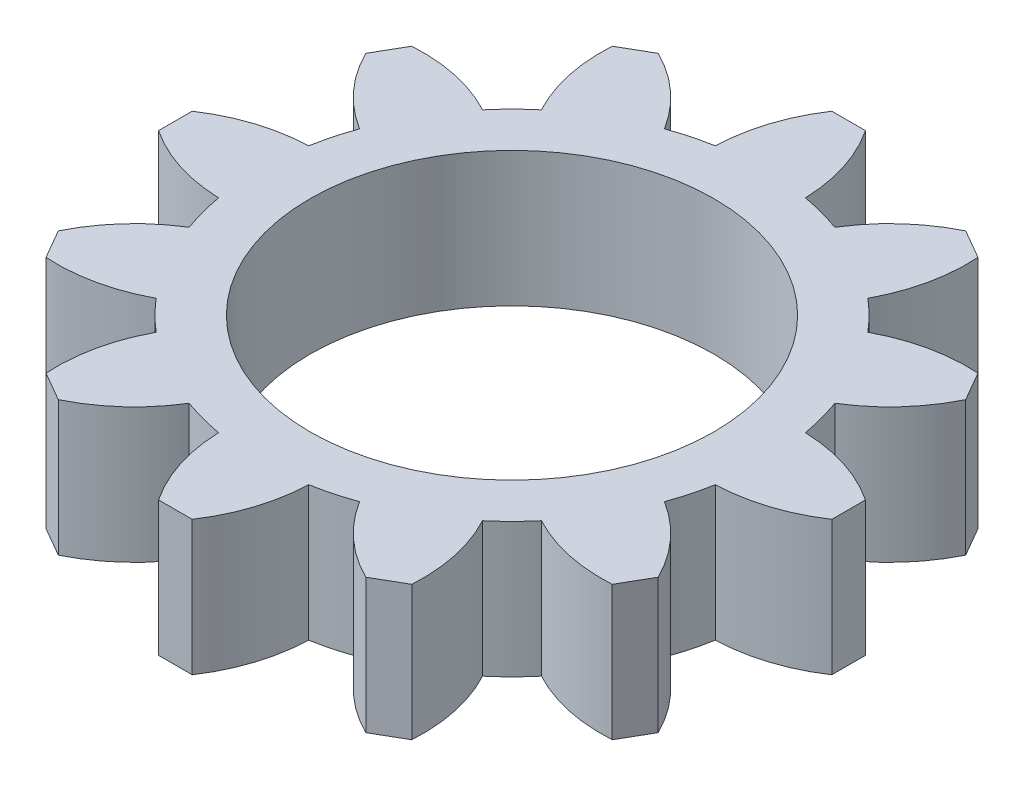
SolidWorks part; units mm, degrees
ref_plane "Front Plane" through (0, 0, 0) normal (0, 0, 1) x (1, 0, 0)
ref_plane "Top Plane" through (0, 0, 0) normal (0, 1, 0) x (1, 0, 0)
ref_plane "Right Plane" through (0, 0, 0) normal (1, 0, 0) x (0, 0, -1)
sketch "Sketch1" plane through (0, 0, 0) normal (0, 1, 0) x (1, 0, 0)
  line L0 (0, 12) -> (0, 21.8422) construction
  line L1 (-1, 20) -> (1, 20)
  line L2 (9.134, 17.8205) -> (10.866, 16.8205)
  line L3 (16.8205, 10.866) -> (17.8205, 9.134)
  line L4 (20, 1) -> (20, -1)
  line L5 (17.8205, -9.134) -> (16.8205, -10.866)
  line L6 (10.866, -16.8205) -> (9.134, -17.8205)
  line L7 (1, -20) -> (-1, -20)
  line L8 (-9.134, -17.8205) -> (-10.866, -16.8205)
  line L9 (-16.8205, -10.866) -> (-17.8205, -9.134)
  line L10 (-20, -1) -> (-20, 1)
  line L11 (-17.8205, 9.134) -> (-16.8205, 10.866)
  line L12 (-10.866, 16.8205) -> (-9.134, 17.8205)
  arc A0 (-2.675, 14.7596) -> (-5.0632, 14.1196) centre (0, 0) ccw
  circle A1 centre (0, 0) radius 12
  arc A2 (-1, 20) -> (-2.675, 14.7596) centre (7.3203, 14.4527) ccw
  arc A3 (1, 20) -> (2.675, 14.7596) centre (-7.3203, 14.4527) cw
  arc A4 (9.134, 17.8205) -> (5.0632, 14.1196) centre (13.5659, 8.8562) ccw
  arc A5 (10.866, 16.8205) -> (9.6964, 11.4446) centre (0.8868, 16.1765) cw
  arc A6 (16.8205, 10.866) -> (11.4446, 9.6964) centre (16.1765, 0.8868) ccw
  arc A7 (17.8205, 9.134) -> (14.1196, 5.0632) centre (8.8562, 13.5659) cw
  arc A8 (20, 1) -> (14.7596, 2.675) centre (14.4527, -7.3203) ccw
  arc A9 (20, -1) -> (14.7596, -2.675) centre (14.4527, 7.3203) cw
  arc A10 (17.8205, -9.134) -> (14.1196, -5.0632) centre (8.8562, -13.5659) ccw
  arc A11 (16.8205, -10.866) -> (11.4446, -9.6964) centre (16.1765, -0.8868) cw
  arc A12 (10.866, -16.8205) -> (9.6964, -11.4446) centre (0.8868, -16.1765) ccw
  arc A13 (9.134, -17.8205) -> (5.0632, -14.1196) centre (13.5659, -8.8562) cw
  arc A14 (1, -20) -> (2.675, -14.7596) centre (-7.3203, -14.4527) ccw
  arc A15 (-1, -20) -> (-2.675, -14.7596) centre (7.3203, -14.4527) cw
  arc A16 (-9.134, -17.8205) -> (-5.0632, -14.1196) centre (-13.5659, -8.8562) ccw
  arc A17 (-10.866, -16.8205) -> (-9.6964, -11.4446) centre (-0.8868, -16.1765) cw
  arc A18 (-16.8205, -10.866) -> (-11.4446, -9.6964) centre (-16.1765, -0.8868) ccw
  arc A19 (-17.8205, -9.134) -> (-14.1196, -5.0632) centre (-8.8562, -13.5659) cw
  arc A20 (-20, -1) -> (-14.7596, -2.675) centre (-14.4527, 7.3203) ccw
  arc A21 (-20, 1) -> (-14.7596, 2.675) centre (-14.4527, -7.3203) cw
  arc A22 (-17.8205, 9.134) -> (-14.1196, 5.0632) centre (-8.8562, 13.5659) ccw
  arc A23 (-16.8205, 10.866) -> (-11.4446, 9.6964) centre (-16.1765, 0.8868) cw
  arc A24 (-10.866, 16.8205) -> (-9.6964, 11.4446) centre (-0.8868, 16.1765) ccw
  arc A25 (-9.134, 17.8205) -> (-5.0632, 14.1196) centre (-13.5659, 8.8562) cw
  arc A26 (14.1196, -5.0632) -> (14.7596, -2.675) centre (0, 0) ccw
  arc A27 (14.7596, 2.675) -> (14.1196, 5.0632) centre (0, 0) ccw
  arc A28 (11.4446, 9.6964) -> (9.6964, 11.4446) centre (0, 0) ccw
  arc A29 (5.0632, 14.1196) -> (2.675, 14.7596) centre (0, 0) ccw
  arc A30 (-9.6964, 11.4446) -> (-11.4446, 9.6964) centre (0, 0) ccw
  arc A31 (-14.1196, 5.0632) -> (-14.7596, 2.675) centre (0, 0) ccw
  arc A32 (-14.7596, -2.675) -> (-14.1196, -5.0632) centre (0, 0) ccw
  arc A33 (-11.4446, -9.6964) -> (-9.6964, -11.4446) centre (0, 0) ccw
  arc A34 (-5.0632, -14.1196) -> (-2.675, -14.7596) centre (0, 0) ccw
  arc A35 (2.675, -14.7596) -> (5.0632, -14.1196) centre (0, 0) ccw
  arc A36 (9.6964, -11.4446) -> (11.4446, -9.6964) centre (0, 0) ccw
  point P80 (0, 0)
  dimension "D1" = 30
  dimension "D2" = 24
  dimension "D6" = 10
  dimension "D8" = 12
  dimension "D3" = 2
  dimension "D4" = 20
  dimension "D5" = 2
  dimension "D7" = 5.35
extrude "Boss-Extrude1" add sketch "Sketch1" along normal blind 8
